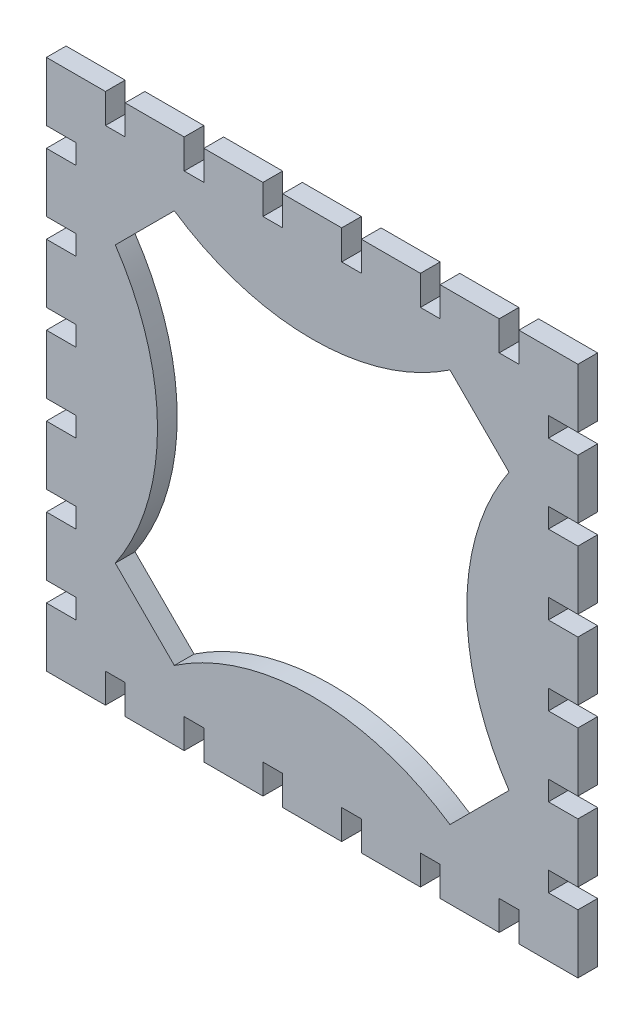
SolidWorks part; units mm, degrees
ref_plane "Front Plane" through (0, 0, 0) normal (0, 0, 1) x (1, 0, 0)
ref_plane "Top Plane" through (0, 0, 0) normal (0, 1, 0) x (1, 0, 0)
ref_plane "Right Plane" through (0, 0, 0) normal (1, 0, 0) x (0, 0, -1)
sketch "Sketch1" plane through (0, 0, 0) normal (0, 0, 1) x (1, 0, 0)
  line L540 (180, 204) -> (171, 213)
  line L541 (171, 255) -> (180, 264)
  line L542 (222, 264) -> (231, 255)
  line L543 (231, 213) -> (222, 204)
  line L544 (237, 253.5) -> (241.5, 253.5)
  line L545 (241.5, 253.5) -> (241.5, 262.5)
  line L546 (241.5, 262.5) -> (237, 262.5)
  line L547 (237, 262.5) -> (237, 265.5)
  line L548 (237, 265.5) -> (241.5, 265.5)
  line L549 (241.5, 265.5) -> (241.5, 274.5)
  line L550 (241.5, 274.5) -> (232.5, 274.5)
  line L551 (232.5, 274.5) -> (232.5, 270)
  line L552 (232.5, 270) -> (229.5, 270)
  line L553 (229.5, 270) -> (229.5, 274.5)
  line L554 (229.5, 274.5) -> (220.5, 274.5)
  line L555 (220.5, 274.5) -> (220.5, 270)
  line L556 (220.5, 270) -> (217.5, 270)
  line L557 (217.5, 270) -> (217.5, 274.5)
  line L558 (217.5, 274.5) -> (208.5, 274.5)
  line L559 (208.5, 274.5) -> (208.5, 270)
  line L560 (208.5, 270) -> (205.5, 270)
  line L561 (205.5, 270) -> (205.5, 274.5)
  line L562 (205.5, 274.5) -> (196.5, 274.5)
  line L563 (196.5, 274.5) -> (196.5, 270)
  line L564 (196.5, 270) -> (193.5, 270)
  line L565 (193.5, 270) -> (193.5, 274.5)
  line L566 (193.5, 274.5) -> (184.5, 274.5)
  line L567 (184.5, 274.5) -> (184.5, 270)
  line L568 (184.5, 270) -> (181.5, 270)
  line L569 (181.5, 270) -> (181.5, 274.5)
  line L570 (181.5, 274.5) -> (172.5, 274.5)
  line L571 (172.5, 274.5) -> (172.5, 270)
  line L572 (172.5, 270) -> (169.5, 270)
  line L573 (169.5, 270) -> (169.5, 274.5)
  line L574 (169.5, 274.5) -> (160.5, 274.5)
  line L575 (160.5, 274.5) -> (160.5, 265.5)
  line L576 (160.5, 265.5) -> (165, 265.5)
  line L577 (165, 265.5) -> (165, 262.5)
  line L578 (165, 262.5) -> (160.5, 262.5)
  line L579 (160.5, 262.5) -> (160.5, 253.5)
  line L580 (160.5, 253.5) -> (165, 253.5)
  line L581 (165, 253.5) -> (165, 250.5)
  line L582 (165, 250.5) -> (160.5, 250.5)
  line L583 (160.5, 250.5) -> (160.5, 241.5)
  line L584 (160.5, 241.5) -> (165, 241.5)
  line L585 (165, 241.5) -> (165, 238.5)
  line L586 (165, 238.5) -> (160.5, 238.5)
  line L587 (160.5, 238.5) -> (160.5, 229.5)
  line L588 (160.5, 229.5) -> (165, 229.5)
  line L589 (165, 229.5) -> (165, 226.5)
  line L590 (165, 226.5) -> (160.5, 226.5)
  line L591 (160.5, 226.5) -> (160.5, 217.5)
  line L592 (160.5, 217.5) -> (165, 217.5)
  line L593 (165, 217.5) -> (165, 214.5)
  line L594 (165, 214.5) -> (160.5, 214.5)
  line L595 (160.5, 214.5) -> (160.5, 205.5)
  line L596 (160.5, 205.5) -> (165, 205.5)
  line L597 (165, 205.5) -> (165, 202.5)
  line L598 (165, 202.5) -> (160.5, 202.5)
  line L599 (160.5, 202.5) -> (160.5, 193.5)
  line L600 (160.5, 193.5) -> (169.5, 193.5)
  line L601 (169.5, 193.5) -> (169.5, 198)
  line L602 (169.5, 198) -> (172.5, 198)
  line L603 (172.5, 198) -> (172.5, 193.5)
  line L604 (172.5, 193.5) -> (181.5, 193.5)
  line L605 (181.5, 193.5) -> (181.5, 198)
  line L606 (181.5, 198) -> (184.5, 198)
  line L607 (184.5, 198) -> (184.5, 193.5)
  line L608 (184.5, 193.5) -> (193.5, 193.5)
  line L609 (193.5, 193.5) -> (193.5, 198)
  line L610 (193.5, 198) -> (196.5, 198)
  line L611 (196.5, 198) -> (196.5, 193.5)
  line L612 (196.5, 193.5) -> (205.5, 193.5)
  line L613 (205.5, 193.5) -> (205.5, 198)
  line L614 (205.5, 198) -> (208.5, 198)
  line L615 (208.5, 198) -> (208.5, 193.5)
  line L616 (208.5, 193.5) -> (217.5, 193.5)
  line L617 (217.5, 193.5) -> (217.5, 198)
  line L618 (217.5, 198) -> (220.5, 198)
  line L619 (220.5, 198) -> (220.5, 193.5)
  line L620 (220.5, 193.5) -> (229.5, 193.5)
  line L621 (229.5, 193.5) -> (229.5, 198)
  line L622 (229.5, 198) -> (232.5, 198)
  line L623 (232.5, 198) -> (232.5, 193.5)
  line L624 (232.5, 193.5) -> (241.5, 193.5)
  line L625 (241.5, 193.5) -> (241.5, 202.5)
  line L626 (241.5, 202.5) -> (237, 202.5)
  line L627 (237, 202.5) -> (237, 205.5)
  line L628 (237, 205.5) -> (241.5, 205.5)
  line L629 (241.5, 205.5) -> (241.5, 214.5)
  line L630 (241.5, 214.5) -> (237, 214.5)
  line L631 (237, 214.5) -> (237, 217.5)
  line L632 (237, 217.5) -> (241.5, 217.5)
  line L633 (241.5, 217.5) -> (241.5, 226.5)
  line L634 (241.5, 226.5) -> (237, 226.5)
  line L635 (237, 226.5) -> (237, 229.5)
  line L636 (237, 229.5) -> (241.5, 229.5)
  line L637 (241.5, 229.5) -> (241.5, 238.5)
  line L638 (241.5, 238.5) -> (237, 238.5)
  line L639 (237, 238.5) -> (237, 241.5)
  line L640 (237, 241.5) -> (241.5, 241.5)
  line L641 (241.5, 241.5) -> (241.5, 250.5)
  line L642 (241.5, 250.5) -> (237, 250.5)
  line L643 (237, 250.5) -> (237, 253.5)
  arc A0 (222, 204) -> (180, 204) centre (201, 172.9315) ccw
  arc A1 (171, 213) -> (171, 255) centre (139.9315, 234) ccw
  arc A2 (180, 264) -> (222, 264) centre (201, 295.0685) ccw
  arc A3 (231, 255) -> (231, 213) centre (262.0685, 234) ccw
extrude "Boss-Extrude1" add sketch "Sketch1" along normal blind 3
